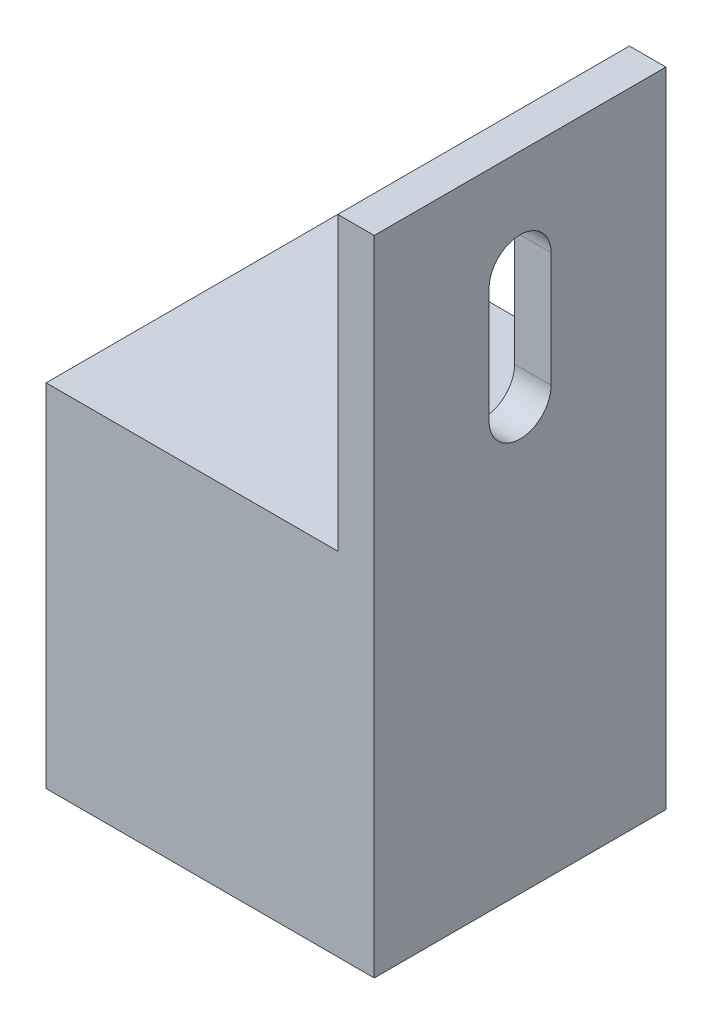
SolidWorks part; units mm, degrees
ref_plane "Front Plane" through (0, 0, 0) normal (0, 0, 1) x (1, 0, 0)
ref_plane "Top Plane" through (0, 0, 0) normal (0, 1, 0) x (1, 0, 0)
ref_plane "Right Plane" through (0, 0, 0) normal (1, 0, 0) x (0, 0, -1)
sketch "Sketch1" plane through (0, 0, 0) normal (0, 1, 0) x (1, 0, 0)
  line L1 (-12.7, 12.7) -> (12.7, 12.7)
  line L2 (-12.7, 12.7) -> (-12.7, -12.7)
  line L3 (-12.7, -12.7) -> (12.7, -12.7)
  line L4 (12.7, 12.7) -> (12.7, -12.7)
  line L5 (-12.7, 12.7) -> (12.7, -12.7) construction
  line L6 (-12.7, -12.7) -> (12.7, 12.7) construction
  point P0 (0, 0)
  dimension "D1" = 25.4
extrude "Boss-Extrude1" add sketch "Sketch1" along normal blind 30.6
sketch "Sketch2" plane through (12.7, 0, 0) normal (1, 0, 0) x (0, 0, -1)
  line L0 (12.7, 30.6) -> (12.7, 0) construction
  line L1 (-12.7, 0) -> (12.7, 0)
  line L2 (-12.7, 0) -> (-12.7, 56)
  line L3 (-12.7, 56) -> (12.7, 56)
  line L4 (12.7, 0) -> (12.7, 56)
  line L5 (0, 47) -> (0, 37) construction
  line L6 (2.7, 47) -> (2.7, 37)
  line L7 (-2.7, 47) -> (-2.7, 37)
  arc A0 (2.7, 47) -> (-2.7, 47) centre (0, 47) ccw
  arc A1 (-2.7, 37) -> (2.7, 37) centre (0, 37) ccw
  point P9 (0, 42)
  point P15 (-2.7, 44.9857)
  point P17 (0, 0)
  point P18 (0, 27.7121)
  dimension "D2" = 2.7
  dimension "D1" = 56
  dimension "D3" = 10
  dimension "D4" = 14
extrude "Boss-Extrude2" add sketch "Sketch2" along normal blind 3.175
